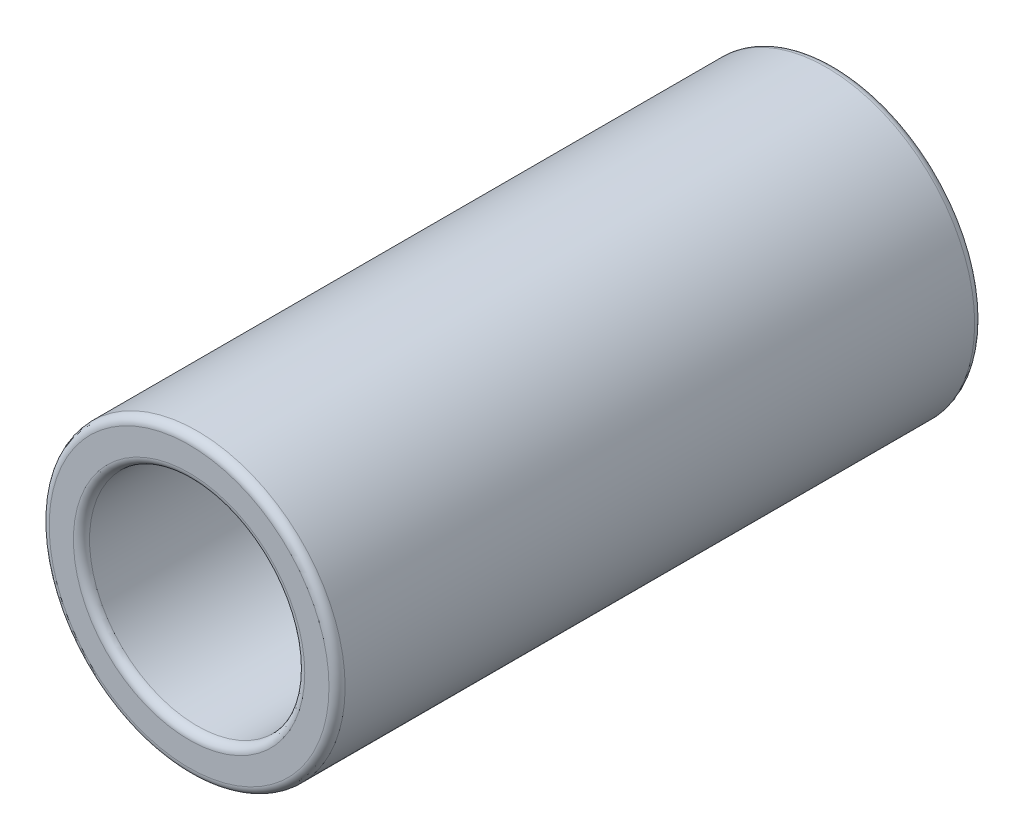
SolidWorks part; units mm, degrees
ref_plane "Alzado" through (0, 0, 0) normal (0, 0, 1) x (1, 0, 0)
ref_plane "Planta" through (0, 0, 0) normal (0, 1, 0) x (1, 0, 0)
ref_plane "Vista lateral" through (0, 0, 0) normal (1, 0, 0) x (0, 0, -1)
sketch "Croquis1" plane through (0, 0, 0) normal (0, 0, 1) x (1, 0, 0)
  circle A0 centre (0, 0) radius 5.5
  circle A1 centre (0, 0) radius 4
  dimension "D1" = 11
  dimension "D2" = 8
extrude "Saliente-Extruir1" add sketch "Croquis1" along normal blind 24
fillet "Redondeo1" radius 0.3 4 edges at (5.5, 0, 0) (4, 0, 0) (4, 0, 24) (5.5, 0, 24)
